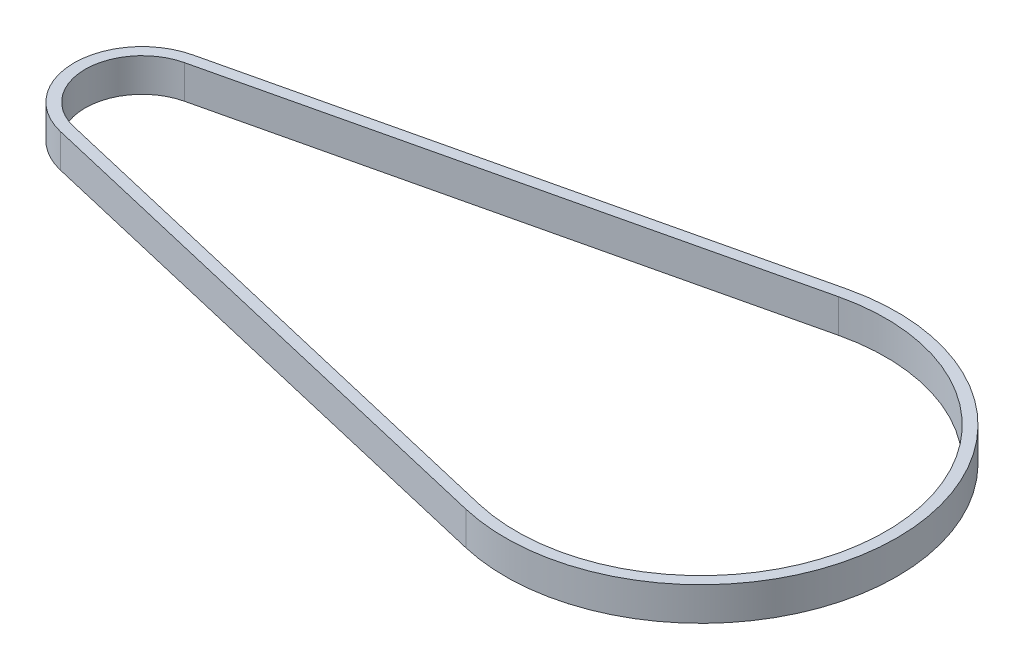
SolidWorks part; units mm, degrees
material "Rubber"
ref_plane "Front Plane" through (0, 0, 0) normal (0, 0, 1) x (1, 0, 0)
ref_plane "Top Plane" through (0, 0, 0) normal (0, 1, 0) x (1, 0, 0)
ref_plane "Right Plane" through (0, 0, 0) normal (1, 0, 0) x (0, 0, -1)
sketch "Sketch1" plane through (0, 0, 0) normal (0, 1, 0) x (1, 0, 0)
  line L0 (-51.2855, 4.9651) -> (-3.7808, 16.1123)
  line L1 (-50.1204, 0) -> (0, 0) construction
  line L2 (-51.2855, -4.9651) -> (-3.7808, -16.1123)
  line L3 (-51.5139, 5.9387) -> (-4.0093, 17.0859)
  line L4 (-51.5139, -5.9387) -> (-4.0093, -17.0859)
  arc A0 (-3.7808, -16.1123) -> (-3.7808, 16.1123) centre (0, 0) ccw
  arc A1 (-51.2855, 4.9651) -> (-51.2855, -4.9651) centre (-50.1204, 0) ccw
  arc A2 (-4.0093, -17.0859) -> (-4.0093, 17.0859) centre (0, 0) ccw
  arc A3 (-51.5139, 5.9387) -> (-51.5139, -5.9387) centre (-50.1204, 0) ccw
  dimension "D1" = 16.55
  dimension "D2" = 5.1
  dimension "D3" = 50.1204
  dimension "D4" = 1
extrude "Boss-Extrude1" add sketch "Sketch1" along normal blind 3
